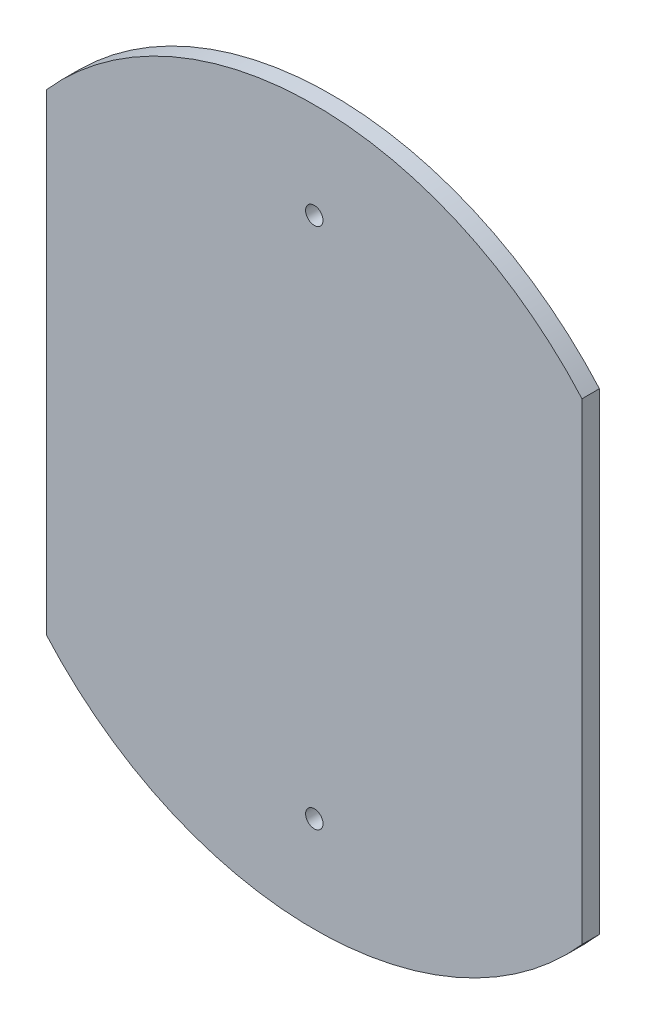
SolidWorks part; units mm, degrees
ref_plane "Front Plane" through (0, 0, 0) normal (0, 0, 1) x (1, 0, 0)
ref_plane "Top Plane" through (0, 0, 0) normal (0, 1, 0) x (1, 0, 0)
ref_plane "Right Plane" through (0, 0, 0) normal (1, 0, 0) x (0, 0, -1)
sketch "Sketch1" plane through (0, 0, 0) normal (0, 0, 1) x (1, 0, 0)
  circle A0 centre (0, 0) radius 82
  dimension "D1" = 164
extrude "Boss-Extrude1" add sketch "Sketch1" along normal blind 4
sketch "Sketch2" plane through (0, 0, 4) normal (0, 0, 1) x (1, 0, 0)
  circle A0 centre (0, 60) radius 2
  dimension "D1" = 4
  dimension "D2" = 60
extrude "Cut-Extrude1" cut sketch "Sketch2" against normal blind 8
pattern_circular "CirPattern1" count 2 every 180 about axis through (0, 0, 0) along (0, 0, 1) of "Cut-Extrude1"
sketch "Sketch3" plane through (0, 0, 4) normal (0, 0, 1) x (1, 0, 0)
  line L0 (0, 0) -> (73.0625, -37.2272)
  line L1 (0, 0) -> (61.4795, 31.3253)
  line L2 (0, 0) -> (82, 0) construction
  line L3 (61.4795, 31.3253) -> (61.4795, -54.2612)
  line L4 (61.4795, -54.2612) -> (61.4795, 54.2612)
  line L5 (0, -2.2) -> (0, 2.2) construction
  line L6 (-61.4795, -54.2612) -> (-61.4795, 54.2612)
  circle A0 centre (0, 0) radius 82 construction
  arc A1 (61.4795, -54.2612) -> (61.4795, 54.2612) centre (0, 0) ccw
  arc A4 (61.4795, -31.3253) -> (61.4795, 31.3253) centre (0, 0) ccw
  circle M9 centre (0, 0) radius 82
  dimension "D3" = 138
  dimension "D1" = 27
  dimension "D2" = 27
extrude "Cut-Extrude2" cut sketch "Sketch3" against normal blind 10 and the other way through all contours L6 M9 | A4 L2 A1 L4 | L3 L2 A4 | L2 L4 A4 | L2 A4 L0 M9 | L0 L3 M9
